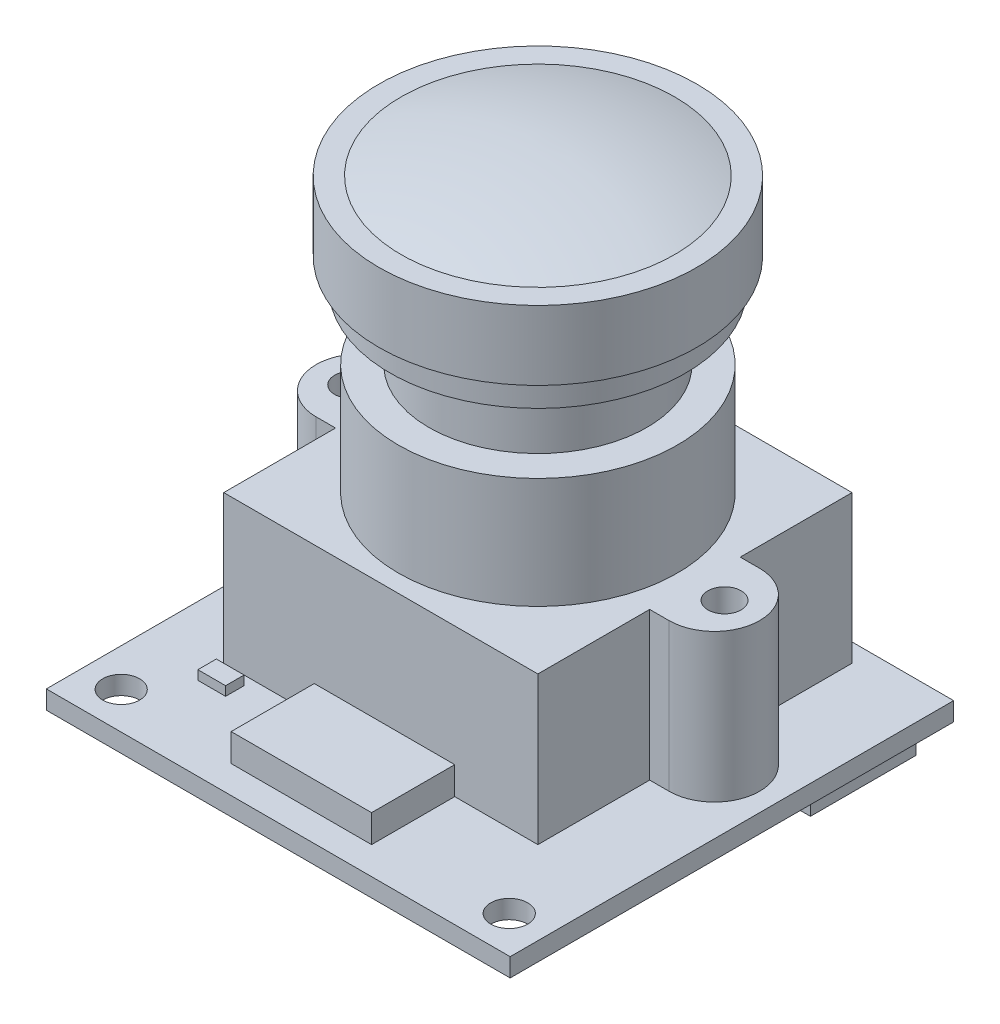
SolidWorks part; units mm, degrees
ref_plane "Front Plane" through (0, 0, 0) normal (0, 0, 1) x (1, 0, 0)
ref_plane "Top Plane" through (0, 0, 0) normal (0, 1, 0) x (1, 0, 0)
ref_plane "Right Plane" through (0, 0, 0) normal (1, 0, 0) x (0, 0, -1)
sketch "Sketch1" plane through (0, 0, 0) normal (1, 0, 0) x (0, 0, -1)
  line L0 (0, 0) -> (0, 30.3805) construction
  line L1 (0, 0) -> (0, 16)
  line L2 (7.4, 14.85) -> (8.6, 14.85)
  line L3 (8.6, 14.85) -> (8.6, 11.1)
  line L4 (8.6, 11.1) -> (8, 11.1)
  line L5 (8, 11.1) -> (8, 9.6)
  line L6 (8, 9.6) -> (5.9, 9.6)
  line L7 (5.9, 9.6) -> (5.9, 6)
  line L8 (5.9, 6) -> (7.55, 6)
  line L9 (7.55, 6) -> (7.55, 0)
  line L10 (7.55, 0) -> (0, 0)
  line L11 (0, 16) -> (-17.9797, 16) construction
  arc A0 (0, 16) -> (7.4, 14.85) centre (0, -8.3837) cw
  dimension "D1" = 7.55
  dimension "D2" = 6
  dimension "D3" = 5.9
  dimension "D4" = 8
  dimension "D5" = 3.75
  dimension "D6" = 8.6
  dimension "D7" = 3.6
  dimension "D8" = 1.5
  dimension "D9" = 16
  dimension "D10" = 1.2
revolve "Revolve1" add sketch "Sketch1" angle 360 about L0
sketch "Sketch2" plane through (0, 0, 0) normal (0, -1, 0) x (1, 0, 0)
  line L0 (0, 0) -> (9.55, 0) construction
  line L1 (-8.5, -8.5) -> (8.5, -8.5)
  line L2 (-8.5, -8.5) -> (-8.5, -2.45)
  line L3 (-8.5, 8.5) -> (8.5, 8.5)
  line L4 (8.5, -8.5) -> (8.5, -2.45)
  line L5 (-8.5, -8.5) -> (8.5, 8.5) construction
  line L6 (-8.5, 8.5) -> (8.5, -8.5) construction
  line L7 (0, 0) -> (-9.55, 0) construction
  line L8 (-9.55, 2.45) -> (-8.5, 2.45)
  line L9 (-9.55, -2.45) -> (-8.5, -2.45)
  line L10 (9.55, -2.45) -> (8.5, -2.45)
  line L11 (9.55, 2.45) -> (8.5, 2.45)
  line L12 (-9.55, 0) -> (-12, 0) construction
  line L13 (9.55, 0) -> (12, 0) construction
  line L14 (-10.1, 0) -> (0, -8.5) construction
  line L15 (0, -8.5) -> (10.1, 0) construction
  line L16 (8.5, 2.45) -> (8.5, 8.5)
  line L18 (-8.5, 2.45) -> (-8.5, 8.5)
  circle A0 centre (-10.1, 0) radius 0.9
  circle A1 centre (10.1, 0) radius 0.9
  arc A4 (-9.55, 2.45) -> (-9.55, -2.45) centre (-9.55, 0) ccw
  arc A5 (9.55, -2.45) -> (9.55, 2.45) centre (9.55, 0) ccw
  point P0 (0, 0)
  dimension "D3" = 24
  dimension "D4" = 4.9
  dimension "D6" = 22
  dimension "D5" = 1.8
  dimension "D1" = 17
  dimension "D2" = 17
extrude "Boss-Extrude1" add sketch "Sketch2" along normal blind 8
sketch "Sketch3" plane through (0, 0, -8.5) normal (0, 0, -1) x (-1, 0, 0)
  line L0 (8.5, 0) -> (-8.5, 0) construction
  line L1 (-1.25, 0) -> (1.25, 0)
  line L2 (-1.25, 0) -> (-1.25, 6)
  line L3 (-1.25, 6) -> (1.25, 6)
  line L4 (1.25, 0) -> (1.25, 6)
  line L5 (7.55, 6) -> (-7.55, 6) construction
  line L6 (0, 0) -> (0, 6) construction
  dimension "D1" = 2.5
extrude "Boss-Extrude2" add sketch "Sketch3" against normal up to surface (1.0542 mm away)
sketch "Sketch4" plane through (0, 0, -8.5) normal (0, 0, -1) x (-1, 0, 0)
  line L0 (0, 0) -> (0, 6) construction
  line L1 (1.25, 6) -> (-1.25, 6) construction
  circle A0 centre (0, 3.75) radius 0.5
  dimension "D1" = 1
  dimension "D2" = 3.75
extrude "Cut-Extrude1" cut sketch "Sketch4" against normal blind 8
sketch "Sketch5" plane through (0, -8, 0) normal (0, -1, 0) x (1, 0, 0)
  line L0 (-8.5, -8.5) -> (8.5, -8.5) construction
  line L1 (13, -9.5) -> (-12.1, -9.5)
  line L2 (13, -9.5) -> (13, 14.5)
  line L3 (13, 14.5) -> (-12.1, 14.5)
  line L4 (-12.1, -9.5) -> (-12.1, 14.5)
  line L5 (8.5, 8.5) -> (-8.5, 8.5) construction
  line L6 (0, 0) -> (0, 21.7665) construction
  line L7 (8.5, 2.45) -> (8.5, 8.5) construction
  line L8 (-8.5, 8.5) -> (-8.5, 2.45) construction
  dimension "D1" = 1
  dimension "D2" = 6
  dimension "D3" = 24
  dimension "D4" = 25.1
  dimension "D5" = 4.5
  dimension "D6" = 3.6
extrude "Boss-Extrude3" add sketch "Sketch5" along normal blind 1
sketch "Sketch6" plane through (0, -8, 0) normal (0, 1, 0) x (1, 0, 0)
  line L0 (0, -8.6) -> (0, -15.9592) construction
  line L1 (8.5, -8.5) -> (-8.5, -8.5) construction
  line L2 (-3.6, -8.5) -> (4, -8.5)
  line L3 (-3.6, -8.5) -> (-3.6, -13)
  line L4 (-3.6, -13) -> (4, -13)
  line L5 (4, -8.5) -> (4, -13)
  line L6 (13, -14.5) -> (-12.1, -14.5) construction
  line L7 (-12.1, -14.5) -> (-12.1, 9.5) construction
  circle A0 centre (0, 0) radius 8.6 construction
  dimension "D1" = 1.5
  dimension "D2" = 7.6
  dimension "D3" = 8.5
extrude "Boss-Extrude4" add sketch "Sketch6" along normal blind 1.5
sketch "Sketch7" plane through (0, -8, 0) normal (0, 1, 0) x (1, 0, 0)
  line L0 (-10.05, -12.5) -> (10.95, -12.5) construction
  line L1 (-12.1, -14.5) -> (-12.1, 9.5) construction
  line L2 (13, 9.5) -> (13, -14.5) construction
  line L3 (13, -14.5) -> (-12.1, -14.5) construction
  circle A0 centre (-10.05, -12.5) radius 1
  circle A1 centre (10.95, -12.5) radius 1
  dimension "D1" = 23
  dimension "D2" = 2
  dimension "D3" = 1.05
  dimension "D4" = 1.05
  dimension "D5" = 1
extrude "Cut-Extrude2" cut sketch "Sketch7" against normal through all
sketch "Sketch8" plane through (0, -8, 0) normal (0, 1, 0) x (1, 0, 0)
  line L0 (13, -14.5) -> (-12.1, -14.5) construction
  line L1 (-8.4, -9) -> (-6.9, -9)
  line L2 (-8.4, -9) -> (-8.4, -10)
  line L3 (-8.4, -10) -> (-6.9, -10)
  line L4 (-6.9, -9) -> (-6.9, -10)
  line L5 (-12.1, -14.5) -> (-12.1, 9.5) construction
  dimension "D1" = 1.5
  dimension "D2" = 1
  dimension "D3" = 4.5
  dimension "D4" = 3.7
extrude "Boss-Extrude5" add sketch "Sketch8" along normal blind 0.5
sketch "Sketch9" plane through (0, -9, 0) normal (0, -1, 0) x (1, 0, 0)
  line L0 (-12.1, -9.5) -> (13, -9.5) construction
  line L1 (-10.05, -9.5) -> (10.95, -9.5)
  line L2 (-10.05, -9.5) -> (-10.05, -3.8)
  line L3 (-10.05, -3.8) -> (10.95, -3.8)
  line L4 (10.95, -9.5) -> (10.95, -3.8)
  line L5 (0.45, 14.5) -> (0.45, -3.8) construction
  line L6 (13, 14.5) -> (-12.1, 14.5) construction
  dimension "D1" = 5.7
  dimension "D2" = 21
extrude "Boss-Extrude6" add sketch "Sketch9" along normal blind 2.6
